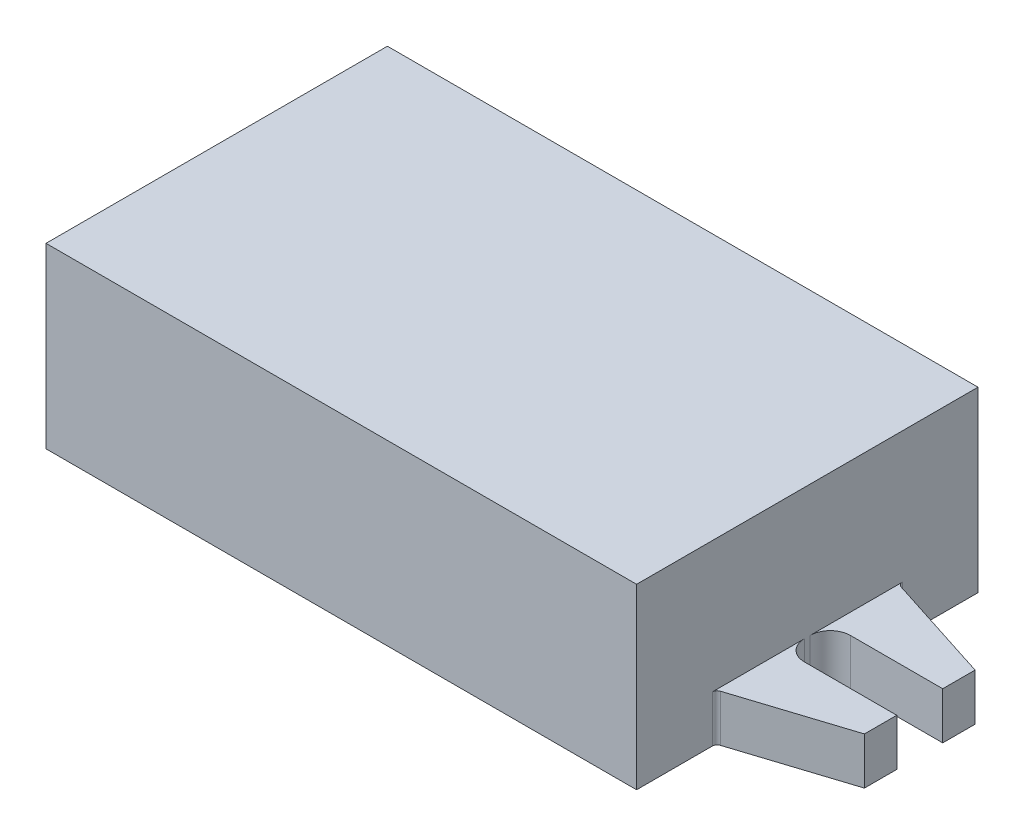
SolidWorks part; units mm, degrees
ref_plane "Front Plane" through (0, 0, 0) normal (0, 0, 1) x (1, 0, 0)
ref_plane "Top Plane" through (0, 0, 0) normal (0, 1, 0) x (1, 0, 0)
ref_plane "Right Plane" through (0, 0, 0) normal (1, 0, 0) x (0, 0, -1)
sketch "Sketch1" plane through (0, 0, 0) normal (0, 1, 0) x (1, 0, 0)
  line L0 (23.1775, 26.797) -> (23.1775, 0) construction
  line L1 (0, 0) -> (46.355, 0)
  line L3 (0, 26.797) -> (46.355, 26.797)
  line L4 (46.355, 20.8519) -> (46.355, 26.797)
  line L5 (23.1775, 13.3985) -> (69.7604, 13.3985) construction
  line L6 (-8.8265, 17.7419) -> (-8.8265, 15.2019)
  line L7 (-8.8265, 11.5951) -> (-8.8265, 9.0551)
  line L8 (55.1815, 17.7419) -> (55.1815, 15.2019)
  line L9 (55.1815, 11.5951) -> (55.1815, 9.0551)
  line L10 (-8.8265, 9.0551) -> (55.1815, 9.0551) construction
  line L11 (-8.8265, 15.2019) -> (-8.8265, 11.5951) construction
  line L12 (55.1815, 15.2019) -> (55.1815, 11.5951) construction
  line L13 (-8.8265, 17.7419) -> (-0.2646, 20.4891)
  line L14 (-8.8265, 9.0551) -> (-0.2646, 6.3079)
  line L15 (55.1815, 17.7419) -> (46.6196, 20.4891)
  line L16 (55.1815, 9.0551) -> (46.6196, 6.3079)
  line L17 (-8.8265, 15.2019) -> (-1.5748, 15.2019)
  line L18 (-8.8265, 11.5951) -> (-1.5748, 11.5951)
  line L19 (47.9298, 15.2019) -> (55.1815, 15.2019)
  line L20 (55.1815, 11.5951) -> (47.9298, 11.5951)
  line L21 (46.355, 5.9451) -> (46.355, 0)
  line L22 (46.355, 13.1699) -> (46.355, 13.6271)
  line L23 (0, 26.797) -> (0, 20.8519)
  line L24 (0, 5.9451) -> (0, 0)
  line L25 (0, 13.1699) -> (0, 13.6271)
  arc A0 (47.9298, 11.5951) -> (46.355, 13.1699) centre (47.9298, 13.1699) cw
  arc A1 (47.9298, 15.2019) -> (46.355, 13.6271) centre (47.9298, 13.6271) ccw
  arc A2 (-1.5748, 11.5951) -> (0, 13.1699) centre (-1.5748, 13.1699) ccw
  arc A3 (-1.5748, 15.2019) -> (0, 13.6271) centre (-1.5748, 13.6271) cw
  arc A4 (-0.2646, 6.3079) -> (0, 5.9451) centre (-0.381, 5.9451) cw
  arc A5 (46.6196, 6.3079) -> (46.355, 5.9451) centre (46.736, 5.9451) ccw
  arc A6 (46.6196, 20.4891) -> (46.355, 20.8519) centre (46.736, 20.8519) cw
  arc A7 (-0.2646, 20.4891) -> (0, 20.8519) centre (-0.381, 20.8519) ccw
  point P18 (23.1775, 9.0551)
  point P19 (-8.8265, 13.3985)
  point P20 (55.1815, 13.3985)
  point P26 (0, 0)
  point P30 (46.355, 15.0475)
  point P32 (46.355, 11.5951)
  point P35 (46.355, 15.2019)
  point P42 (0, 6.223)
  point P45 (46.355, 6.223)
  point P48 (46.355, 20.574)
  point P51 (0, 20.574)
  dimension "D8" = 1.5748
  dimension "D9" = 0.381
  dimension "D1" = 26.797
  dimension "D2" = 64.008
  dimension "D3" = 46.355
  dimension "D4" = 2.54
  dimension "D5" = 3.6068
  dimension "D6" = 6.223
  dimension "D7" = 6.223
extrude "Boss-Extrude1" add sketch "Sketch1" along normal blind 3.683
sketch "Sketch2" plane through (0, 3.683, 0) normal (0, 1, 0) x (1, 0, 0)
  line L1 (0, 26.797) -> (46.355, 26.797)
  line L2 (0, 26.797) -> (0, 0)
  line L3 (0, 0) -> (46.355, 0)
  line L4 (46.355, 26.797) -> (46.355, 0)
extrude "Boss-Extrude2" add sketch "Sketch2" along normal blind 10.287
